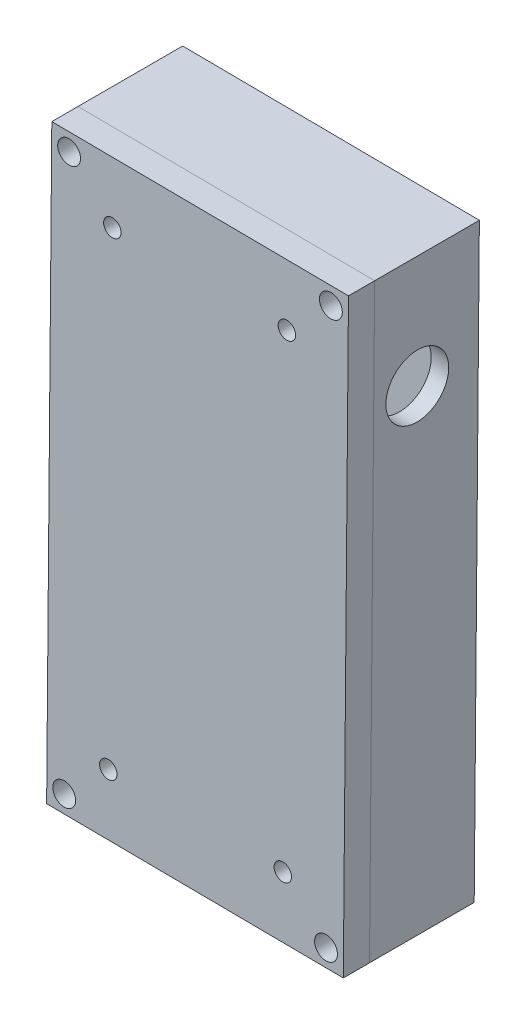
SolidWorks part; units mm, degrees
ref_plane "Front Plane" through (0, 0, 0) normal (0, 0, 1) x (1, 0, 0)
ref_plane "Top Plane" through (0, 0, 0) normal (0, 1, 0) x (1, 0, 0)
ref_plane "Right Plane" through (0, 0, 0) normal (1, 0, 0) x (0, 0, -1)
sketch "Sketch1" plane through (0, 0, 0) normal (0, 0, 1) x (1, 0, 0)
  line L8 (2, 34) -> (2, -34)
  line L9 (2, -34) -> (36, -34)
  line L10 (36, -34) -> (36, 34)
  line L11 (36, 34) -> (2, 34)
sketch "Sketch2" plane through (0, 0, 10) normal (0, 0, 1) x (1, 0, 0)
  line L0 (-9.2949, -44.0272) -> (-8.8244, 9.9708) construction
  line L1 (-9.2949, -44.0272) -> (-8.8244, 9.9708)
  line L4 (22.6429, -51.3058) -> (23.2354, 16.6917)
  line L5 (23.2354, 16.6917) -> (-10.7633, 16.9879)
  line L6 (-10.7633, 16.9879) -> (-11.3558, -51.0095)
  line L7 (-11.3558, -51.0095) -> (22.6429, -51.3058)
  line L8 (22.6429, -51.3058) -> (23.2354, 16.6917)
  line L9 (23.2354, 16.6917) -> (-10.7633, 16.9879)
  line L10 (-10.7633, 16.9879) -> (-11.3558, -51.0095)
  line L11 (-11.3558, -51.0095) -> (22.6429, -51.3058)
  line L12 (15.6606, -49.2448) -> (-4.3386, -49.0706) construction
  line L13 (15.6606, -49.2448) -> (-4.3386, -49.0706)
  line L14 (21.1745, 9.7094) -> (20.704, -44.2886) construction
  line L15 (21.1745, 9.7094) -> (20.704, -44.2886)
  line L17 (-3.781, 14.927) -> (16.2183, 14.7527) construction
  line L18 (-3.781, 14.927) -> (16.2183, 14.7527)
  arc A2 (-9.2949, -44.0272) -> (-4.3386, -49.0706) centre (-4.2951, -44.0708) ccw construction
  arc A6 (-9.2949, -44.0272) -> (-4.3386, -49.0706) centre (-4.2951, -44.0708) ccw
  circle A7 centre (-9.3384, -49.027) radius 0.8115 construction
  circle A8 centre (-9.3384, -49.027) radius 0.8115
  arc A9 (15.6606, -49.2448) -> (20.704, -44.2886) centre (15.7042, -44.245) ccw construction
  circle A10 centre (20.6604, -49.2884) radius 0.8115 construction
  circle A11 centre (20.6604, -49.2884) radius 0.8115
  arc A12 (15.6606, -49.2448) -> (20.704, -44.2886) centre (15.7042, -44.245) ccw
  circle A13 centre (-8.7808, 14.9706) radius 0.8115 construction
  circle A14 centre (21.2181, 14.7092) radius 0.8115 construction
  circle A15 centre (-8.7808, 14.9706) radius 0.8115
  circle A16 centre (21.2181, 14.7092) radius 0.8115
  arc A17 (21.1745, 9.7094) -> (16.2183, 14.7527) centre (16.1747, 9.7529) ccw construction
  arc A18 (21.1745, 9.7094) -> (16.2183, 14.7527) centre (16.1747, 9.7529) ccw
  arc A19 (-3.781, 14.927) -> (-8.8244, 9.9708) centre (-3.8245, 9.9272) ccw construction
  arc A20 (-3.781, 14.927) -> (-8.8244, 9.9708) centre (-3.8245, 9.9272) ccw
  dimension "D1" = 0
extrude "Boss-Extrude1" add sketch "Sketch2" against normal up to surface (12 mm away)
sketch "Sketch3" plane through (0, 0, -2) normal (0, 0, -1) x (-1, 0, 0)
  line L4 (-22.6429, -51.3058) -> (11.3558, -51.0095)
  line L5 (11.3558, -51.0095) -> (10.7633, 16.9879)
  line L6 (10.7633, 16.9879) -> (-23.2354, 16.6917)
  line L7 (-23.2354, 16.6917) -> (-22.6429, -51.3058)
  line L8 (-22.6429, -51.3058) -> (11.3558, -51.0095)
  line L9 (11.3558, -51.0095) -> (10.7633, 16.9879)
  line L10 (10.7633, 16.9879) -> (-23.2354, 16.6917)
  line L11 (-23.2354, 16.6917) -> (-22.6429, -51.3058)
  dimension "D1" = 0
extrude "Boss-Extrude2" add sketch "Sketch3" against normal blind 2
sketch "Sketch4" plane through (-10.9105, 0.0951, 0) normal (-1, 0.0087, 0) x (0, 0, -1)
  line L0 (-5, 44.1065) -> (-5, -9.8935)
  line L4 (2, 51.1065) -> (-10, 51.1065)
  line L5 (-10, 51.1065) -> (-10, -16.8935)
  line L6 (-10, -16.8935) -> (2, -16.8935)
  line L7 (2, -16.8935) -> (2, 51.1065)
  line L8 (2, 51.1065) -> (-10, 51.1065)
  line L9 (-10, 51.1065) -> (-10, -16.8935)
  line L10 (-10, -16.8935) -> (2, -16.8935)
  line L11 (2, -16.8935) -> (2, 51.1065)
  line L13 (0, -9.8935) -> (0, 44.1065)
  line L14 (-10, -9.8935) -> (0, -9.8935)
  line L15 (-10, 44.1065) -> (-10, -9.8935)
  line L16 (0, 44.1065) -> (-10, 44.1065)
  line L17 (0, -9.8935) -> (0, 44.1065)
  line L18 (-10, -9.8935) -> (0, -9.8935)
  line L19 (-10, 44.1065) -> (-10, -9.8935)
  line L20 (0, 44.1065) -> (-10, 44.1065)
  circle A0 centre (-5, 38.1065) radius 3.6
  point P10 (0, 0)
  dimension "D2" = 6
  dimension "D3" = 7.2
  dimension "D1" = 0
  dimension "D4" = 0
extrude "Cut-Extrude1" cut sketch "Sketch4" against normal blind 3
sketch "Sketch5" plane through (23.0882, -0.2012, 0) normal (1, -0.0087, 0) x (0, 0, 1)
  line L0 (10, 17.1065) -> (-2, 17.1065) construction
  line L4 (-2, -16.8935) -> (10, -16.8935)
  line L5 (10, -16.8935) -> (10, 51.1065)
  line L6 (10, 51.1065) -> (-2, 51.1065)
  line L7 (-2, 51.1065) -> (-2, -16.8935)
  line L8 (-2, -16.8935) -> (10, -16.8935)
  line L9 (10, -16.8935) -> (10, 51.1065) construction
  line L10 (10, 51.1065) -> (-2, 51.1065) construction
  line L11 (-2, 51.1065) -> (-2, -16.8935) construction
  circle A0 centre (5, 38.1065) radius 3.6 construction
  circle A1 centre (5, 38.1065) radius 3.6 construction
  circle A2 centre (5, -3.8935) radius 3.6
  dimension "D1" = 0
extrude "Cut-Extrude2" cut sketch "Sketch5" against normal blind 3 contours A2
sketch "Sketch10" plane through (0, 0, 10) normal (0, 0, 1) x (1, 0, 0)
  line L4 (-11.3558, -51.0095) -> (22.6429, -51.3058)
  line L5 (22.6429, -51.3058) -> (23.2354, 16.6917)
  line L6 (23.2354, 16.6917) -> (-10.7633, 16.9879)
  line L7 (-10.7633, 16.9879) -> (-11.3558, -51.0095)
  line L8 (-11.3558, -51.0095) -> (22.6429, -51.3058)
  line L9 (22.6429, -51.3058) -> (23.2354, 16.6917)
  line L10 (23.2354, 16.6917) -> (-10.7633, 16.9879)
  line L11 (-10.7633, 16.9879) -> (-11.3558, -51.0095)
  circle A11 centre (20.6604, -49.2884) radius 1.3115
  circle A12 centre (20.6604, -49.2884) radius 1.3115
  circle A14 centre (21.2181, 14.7092) radius 1.3115
  circle A15 centre (21.2181, 14.7092) radius 1.3115
  circle A17 centre (-8.7808, 14.9706) radius 1.3115
  circle A18 centre (-8.7808, 14.9706) radius 1.3115
  circle A20 centre (-9.3384, -49.027) radius 1.3115
  circle A21 centre (-9.3384, -49.027) radius 1.3115
  dimension "D1" = 0
  dimension "D2" = 0.5
  dimension "D3" = 0.5
  dimension "D4" = 0.5
  dimension "D5" = 0.5
extrude "Boss-Extrude3" add sketch "Sketch10" along normal blind 3 separate body
sketch "Sketch11" plane through (0, 0, 0) normal (0, 0, 1) x (1, 0, 0)
  line L4 (-4.3386, -49.0706) -> (15.6606, -49.2448)
  line L5 (20.704, -44.2886) -> (21.1745, 9.7094)
  line L6 (16.2183, 14.7527) -> (-3.781, 14.927)
  line L7 (-8.8244, 9.9708) -> (-9.2949, -44.0272)
  line L8 (-4.3386, -49.0706) -> (15.6606, -49.2448) construction
  line L9 (20.704, -44.2886) -> (21.1745, 9.7094) construction
  line L10 (16.2183, 14.7527) -> (-3.781, 14.927) construction
  line L11 (-8.8244, 9.9708) -> (-9.2949, -44.0272) construction
  circle A0 centre (16.1747, 9.7529) radius 1
  circle A1 centre (-3.8245, 9.9272) radius 1
  circle A2 centre (15.7042, -44.245) radius 1
  circle A3 centre (-4.2951, -44.0708) radius 1
  arc A4 (-9.2949, -44.0272) -> (-4.3386, -49.0706) centre (-4.2951, -44.0708) ccw
  arc A5 (15.6606, -49.2448) -> (20.704, -44.2886) centre (15.7042, -44.245) ccw
  arc A6 (21.1745, 9.7094) -> (16.2183, 14.7527) centre (16.1747, 9.7529) ccw
  arc A7 (-3.781, 14.927) -> (-8.8244, 9.9708) centre (-3.8245, 9.9272) ccw
  arc A8 (-9.2949, -44.0272) -> (-4.3386, -49.0706) centre (-4.2951, -44.0708) ccw construction
  arc A9 (15.6606, -49.2448) -> (20.704, -44.2886) centre (15.7042, -44.245) ccw construction
  arc A10 (21.1745, 9.7094) -> (16.2183, 14.7527) centre (16.1747, 9.7529) ccw construction
  arc A11 (-3.781, 14.927) -> (-8.8244, 9.9708) centre (-3.8245, 9.9272) ccw construction
  dimension "D2" = 2
  dimension "D1" = 0
extrude "Cut-Extrude3" cut sketch "Sketch11" against normal through all both and the other way through all
